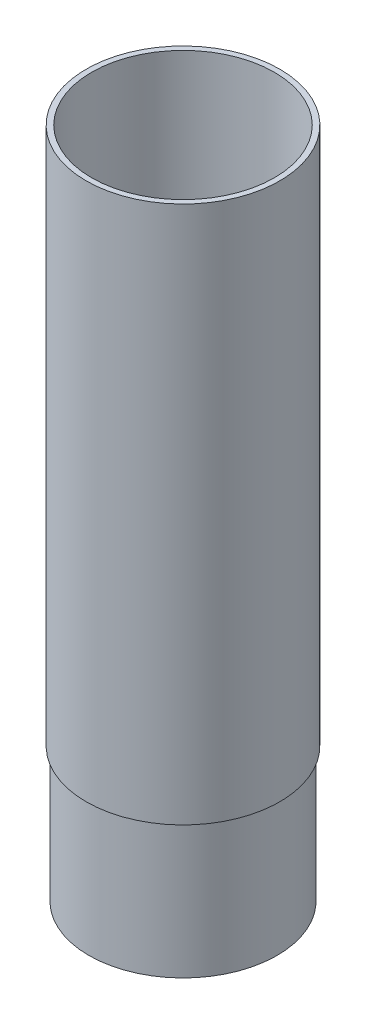
SolidWorks part; units mm, degrees
ref_plane "Plan de face" through (0, 0, 0) normal (0, 0, 1) x (1, 0, 0)
ref_plane "Plan de dessus" through (0, 0, 0) normal (0, 1, 0) x (1, 0, 0)
ref_plane "Plan de droite" through (0, 0, 0) normal (1, 0, 0) x (0, 0, -1)
sketch "Esquisse1" plane through (0, 0, 0) normal (0, 1, 0) x (1, 0, 0)
  circle A0 centre (0, 0) radius 35
extrude "Boss.-Extru.2" add sketch "Esquisse1" along normal blind 250
sketch "Esquisse4" plane through (0, 250, 0) normal (0, 1, 0) x (1, 0, 0)
  circle A0 centre (0, 0) radius 34
extrude "Enlèv. mat.-Extru.3" cut sketch "Esquisse4" against normal blind 250
sketch "Esquisse5" plane through (0, 250, 0) normal (0, 1, 0) x (1, 0, 0)
  circle A0 centre (0, 0) radius 36
extrude "Boss.-Extru.5" add sketch "Esquisse5" along a picked direction on the side against the normal blind 200
sketch "Esquisse6" plane through (0, 250, 0) normal (0, 1, 0) x (1, 0, 0)
  circle A0 centre (0, 0) radius 34
extrude "Enlèv. mat.-Extru.4" cut sketch "Esquisse6" against normal blind 200
